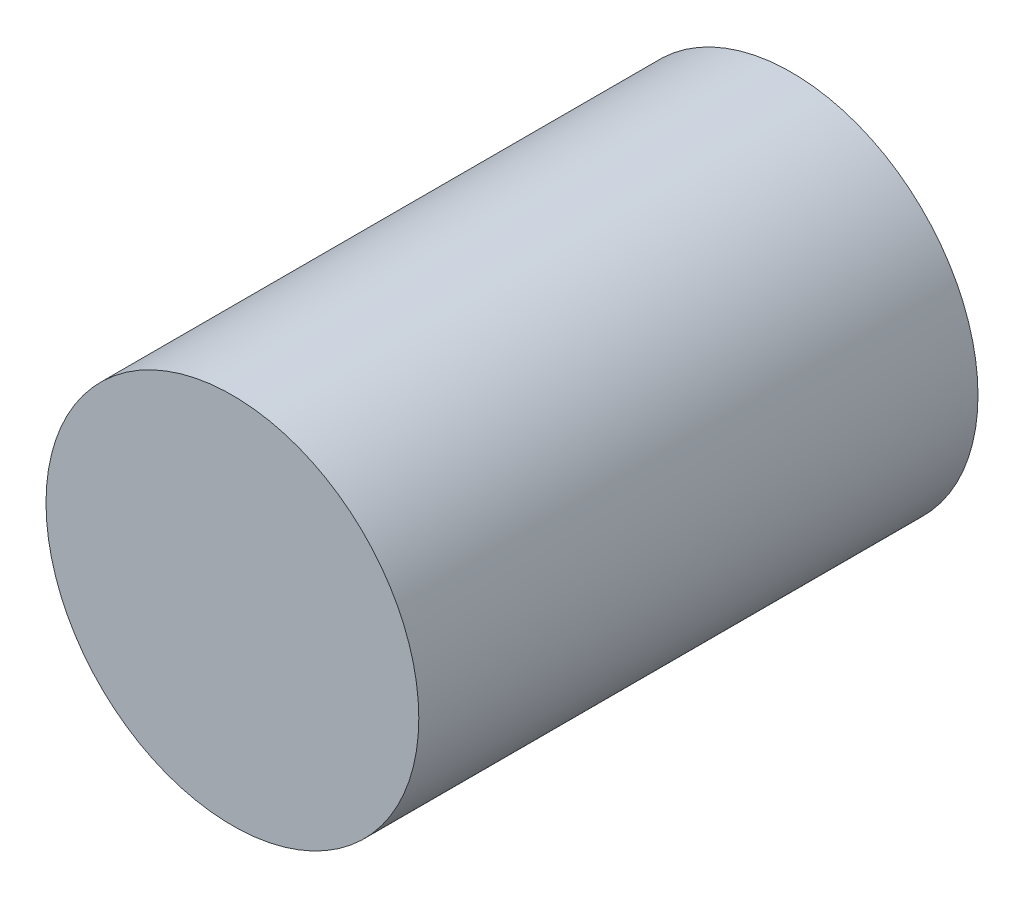
SolidWorks part; units mm, degrees
ref_plane "Front Plane" through (0, 0, 0) normal (0, 0, 1) x (1, 0, 0)
ref_plane "Top Plane" through (0, 0, 0) normal (0, 1, 0) x (1, 0, 0)
ref_plane "Right Plane" through (0, 0, 0) normal (1, 0, 0) x (0, 0, -1)
ref_axis "Axis1" through (0, 0, 55) along (0, 0, -1)
sketch "Sketch1" plane through (0, 0, 0) normal (0, 1, 0) x (1, 0, 0)
  line L1 (-50, -50) -> (0, -50)
  line L2 (-50, -50) -> (-50, 100)
  line L3 (-50, 100) -> (0, 100)
  line L4 (0, -50) -> (0, 100)
revolve "Revolve1" add sketch "Sketch1" angle 360 about axis through (0, 0, 55) along (0, 0, -1)
